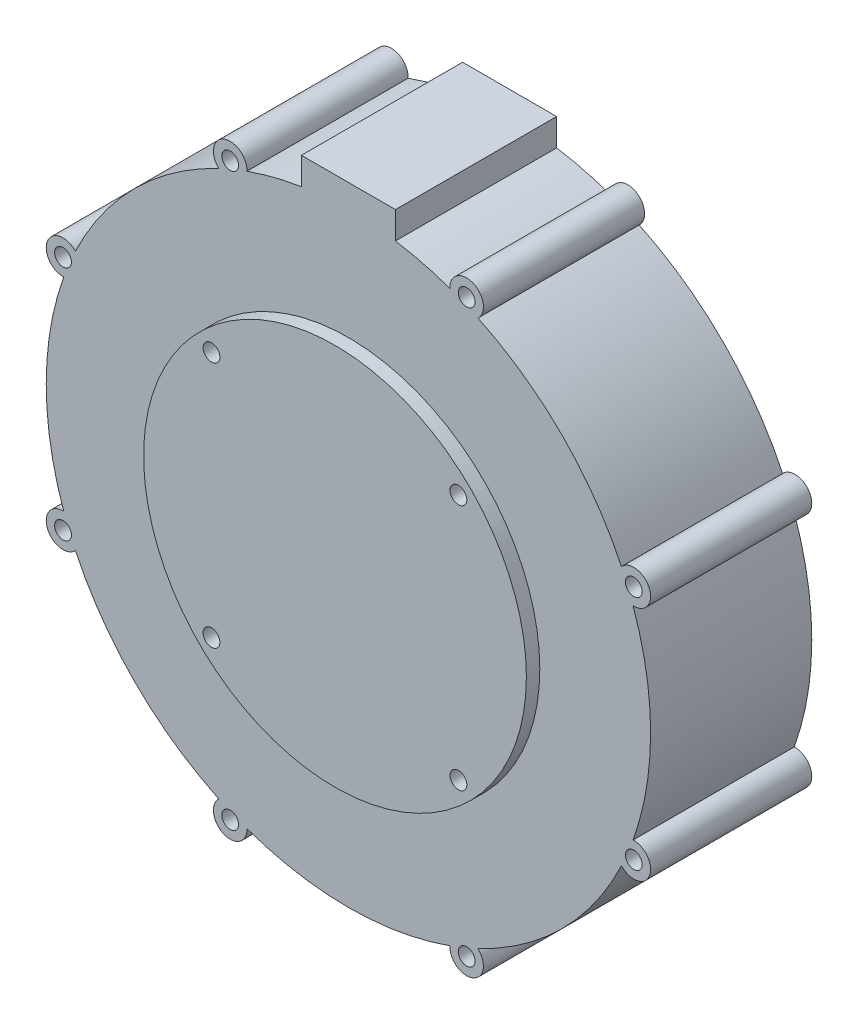
SolidWorks part; units mm, degrees
material "6061 Alloy"
ref_plane "Front Plane" through (0, 0, 0) normal (0, 0, 1) x (1, 0, 0)
ref_plane "Top Plane" through (0, 0, 0) normal (0, 1, 0) x (1, 0, 0)
ref_plane "Right Plane" through (0, 0, 0) normal (1, 0, 0) x (0, 0, -1)
sketch "Sketch1" plane through (0, 0, 0) normal (0, 0, 1) x (1, 0, 0)
  circle A0 centre (0, 0) radius 45
extrude "Than_chinh" add sketch "Sketch1" along normal blind 24
sketch "Sketch2" plane through (0, 0, 0) normal (0, 0, 1) x (1, 0, 0)
  circle A0 centre (42.4985, 17.6034) radius 2.5
  circle A1 centre (17.6034, 42.4985) radius 2.5
  circle A2 centre (-17.6034, 42.4985) radius 2.5
  circle A3 centre (-42.4985, 17.6034) radius 2.5
  circle A4 centre (-42.4985, -17.6034) radius 2.5
  circle A5 centre (-17.6034, -42.4985) radius 2.5
  circle A6 centre (17.6034, -42.4985) radius 2.5
  circle A7 centre (42.4985, -17.6034) radius 2.5
extrude "Vau_bat_vit" add sketch "Sketch2" along normal blind 24
sketch "Sketch3" plane through (0, 0, 0) normal (0, 0, 1) x (1, 0, 0)
  line L1 (-7, 41) -> (7, 41)
  line L2 (-7, 41) -> (-7, 48.5)
  line L3 (-7, 48.5) -> (7, 48.5)
  line L4 (7, 41) -> (7, 48.5)
extrude "Tai_ra_day" add sketch "Sketch3" along normal blind 24
sketch "Sketch4" plane through (0, 0, 24) normal (0, 0, 1) x (1, 0, 0)
  circle A0 centre (42.4985, 17.6034) radius 1.25
  circle A1 centre (17.6034, 42.4985) radius 1.25
  circle A2 centre (-17.6034, 42.4985) radius 1.25
  circle A3 centre (-42.4985, 17.6034) radius 1.25
  circle A4 centre (-42.4985, -17.6034) radius 1.25
  circle A5 centre (-17.6034, -42.4985) radius 1.25
  circle A6 centre (17.6034, -42.4985) radius 1.25
  circle A7 centre (42.4985, -17.6034) radius 1.25
extrude "8xM3_mat_sau" cut sketch "Sketch4" against normal blind 6
sketch "Sketch5" plane through (0, 0, 0) normal (0, 0, -1) x (-1, 0, 0)
  circle A0 centre (-42.4985, 17.6034) radius 1.25
  circle A1 centre (-17.6034, 42.4985) radius 1.25
  circle A2 centre (17.6034, 42.4985) radius 1.25
  circle A3 centre (42.4985, 17.6034) radius 1.25
  circle A4 centre (42.4985, -17.6034) radius 1.25
  circle A5 centre (17.6034, -42.4985) radius 1.25
  circle A6 centre (-17.6034, -42.4985) radius 1.25
  circle A7 centre (-42.4985, -17.6034) radius 1.25
extrude "8xM3_mat_truoc" cut sketch "Sketch5" against normal blind 6
sketch "Sketch6" plane through (0, 0, 24) normal (0, 0, 1) x (1, 0, 0)
  circle A0 centre (0, 0) radius 28.5
extrude "Ong_sau_D57" add sketch "Sketch6" along normal blind 2
sketch "Sketch8" plane through (0, 0, 26) normal (0, 0, 1) x (1, 0, 0)
  circle A0 centre (18.3848, 18.3848) radius 1.25
  circle A1 centre (-18.3848, 18.3848) radius 1.25
  circle A2 centre (-18.3848, -18.3848) radius 1.25
  circle A3 centre (18.3848, -18.3848) radius 1.25
extrude "4xM3_ong_sau" cut sketch "Sketch8" against normal blind 5
sketch "Sketch9" plane through (0, 0, 0) normal (0, 0, -1) x (-1, 0, 0)
  circle A0 centre (0, 0) radius 30
extrude "Bac_D60" add sketch "Sketch9" along normal blind 0.7
sketch "Sketch10" plane through (0, 0, 0) normal (0, 0, -1) x (-1, 0, 0)
  circle A0 centre (0, 0) radius 25
extrude "Go_dinh_vi_D50" add sketch "Sketch10" along normal blind 4.1
sketch "Sketch11" plane through (0, 0, -4.1) normal (0, 0, -1) x (-1, 0, 0)
  circle A0 centre (-12.5, 0) radius 1.25
  circle A1 centre (-6.25, 10.8253) radius 1.25
  circle A2 centre (6.25, 10.8253) radius 1.25
  circle A3 centre (12.5, 0) radius 1.25
  circle A4 centre (6.25, -10.8253) radius 1.25
  circle A5 centre (-6.25, -10.8253) radius 1.25
extrude "6xM3_dau_ra" cut sketch "Sketch11" against normal blind 5
sketch "Sketch12" plane through (0, 0, -4.1) normal (0, 0, -1) x (-1, 0, 0)
  circle A0 centre (0, 10.2) radius 2
  circle A1 centre (8.8335, -5.1) radius 2
  circle A2 centre (-8.8335, -5.1) radius 2
extrude "3xChot_D4" add sketch "Sketch12" along normal blind 3.5
